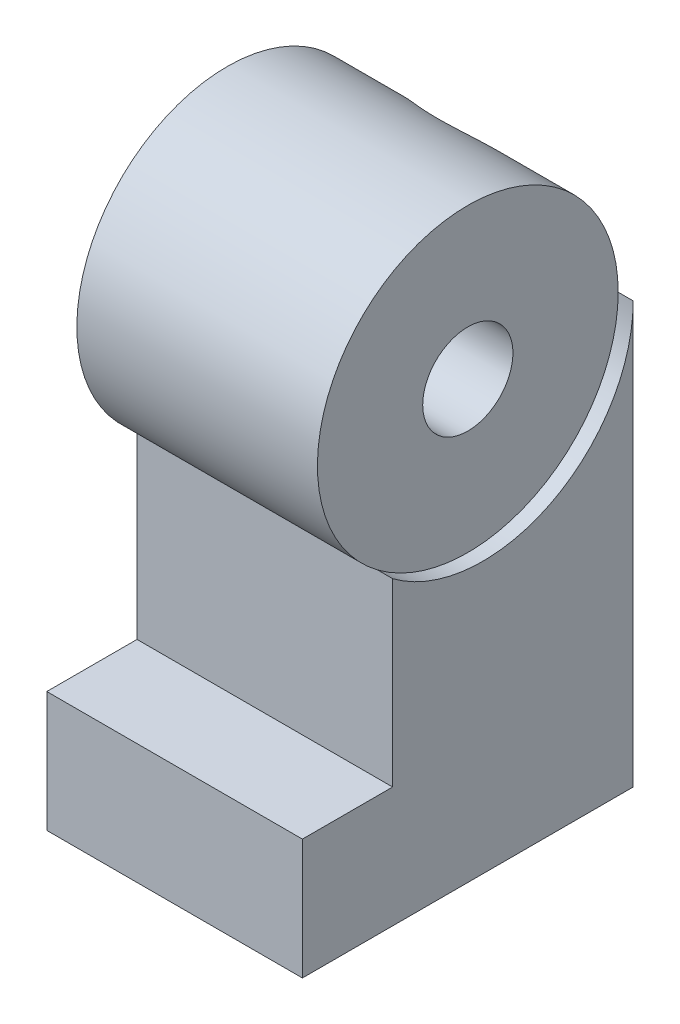
SolidWorks part; units mm, degrees
material "ABS"
ref_plane "Front Plane" through (0, 0, 0) normal (0, 0, 1) x (1, 0, 0)
ref_plane "Top Plane" through (0, 0, 0) normal (0, 1, 0) x (1, 0, 0)
ref_plane "Right Plane" through (0, 0, 0) normal (1, 0, 0) x (0, 0, -1)
sketch "Sketch2" plane through (0, 0, 0) normal (1, 0, 0) x (0, 0, -1)
  line L0 (0, 11.1125) -> (0, 0) construction
  line L1 (-4.3656, 0) -> (4.3656, 0)
  line L2 (-4.3656, 0) -> (-4.3656, 3.175)
  line L3 (-4.3656, 3.175) -> (-1.9844, 3.175)
  line L4 (-1.9844, 3.175) -> (-1.9844, 11.1125)
  line L5 (-1.9844, 11.1125) -> (4.3656, 11.1125)
  line L6 (4.3656, 11.1125) -> (4.3656, 0)
  dimension "D1" = 8.7312
  dimension "D2" = 3.175
  dimension "D3" = 11.1125
  dimension "D4" = 2.3813
extrude "Boss-Extrude4" add sketch "Sketch2" along normal blind 6.7469
sketch "Sketch6" plane through (6.7469, 0, 0) normal (1, 0, 0) x (0, 0, -1)
  line L0 (4.3656, 11.1125) -> (-3.5719, 11.1125) construction
  line L1 (0.3969, 11.1125) -> (0.3969, 15.0813) construction
  circle A0 centre (0.3969, 11.1125) radius 3.9688
  dimension "D1" = 7.9375
  dimension "D2" = 3.9688
extrude "Boss-Extrude5" add sketch "Sketch6" against normal up to surface (6.7469 mm away) up to face at (0, 4.7625, 0.6615)
shell "Shell2" thickness 0.7937
sketch "Sketch7" plane through (0, 0, 0) normal (0, -1, 0) x (1, 0, 0)
  line L0 (5.9531, 3.5719) -> (5.9531, -3.5719) construction
  line L1 (1.1906, -2.3813) -> (5.9531, -2.3813) construction
  line L2 (1.1906, -2.3813) -> (1.1906, 2.3813) construction
  line L3 (1.1906, 2.3813) -> (5.9531, 2.3813) construction
  line L4 (5.9531, -2.3813) -> (5.9531, 2.3813) construction
  line L6 (5.9531, 3.5719) -> (5.9531, 2.3813)
  line L9 (5.9531, 2.3813) -> (1.1906, 2.3813)
  line L10 (0.7937, -3.5719) -> (5.9531, -3.5719)
  line L11 (0.7937, -3.5719) -> (0.7937, 3.5719)
  line L12 (0.7937, 3.5719) -> (5.9531, 3.5719)
  line L14 (1.1906, 2.3813) -> (1.1906, -2.3813)
  line L15 (1.1906, -2.3813) -> (5.9531, -2.3813)
  line L16 (5.9531, -2.3813) -> (5.9531, -3.5719)
  point P4 (5.9531, 0)
  point P17 (1.1906, 0)
  dimension "D1" = 4.7625
extrude "Boss-Extrude6" add sketch "Sketch7" against normal up to next
sketch "Sketch11" plane through (0, 0, 0) normal (-1, 0, 0) x (0, 0, 1)
  circle A0 centre (-0.3969, 11.1125) radius 3.9688
  arc A1 (1.9844, 7.9375) -> (-4.3656, 11.1125) centre (-0.3969, 11.1125) ccw construction
extrude "Cut-Extrude2" cut sketch "Sketch11" against normal offset from surface (0.3969 mm away) 6.35 up to face at (6.7469, 5.0895, 1.0896)
sketch "Sketch13" plane through (6.7469, 0, 0) normal (1, 0, 0) x (0, 0, -1)
  circle A0 centre (0.3969, 11.1125) radius 3.9688
  arc A1 (4.3656, 11.1125) -> (-1.9844, 7.9375) centre (0.3969, 11.1125) ccw construction
extrude "Boss-Extrude11" add sketch "Sketch13" against normal up to surface (6.35 mm away) up to face at (0.3969, 11.1125, -0.3969)
sketch "Sketch14" plane through (0, 0, -4.3656) normal (0, 0, -1) x (-1, 0, 0)
  line L0 (-6.7469, 0) -> (0, 0) construction
  line L1 (-6.7469, 0) -> (-6.7469, 11.1125) construction
  circle A0 centre (-3.5719, 3.9688) radius 2.3813
  circle A1 centre (-3.5719, 11.9062) radius 2.3813
  dimension "D2" = 4.7625
  dimension "D1" = 7.9375
  dimension "D3" = 3.9688
  dimension "D4" = 3.175
extrude "Cut-Extrude3" cut sketch "Sketch14" against normal up to surface (1.9844 mm away) up to face at (3.5719, 3.8377, -2.3812)
sketch "Sketch16" plane through (0, 0, -2.3813) normal (0, 0, -1) x (-1, 0, 0)
  line L0 (-0.3969, 11.1125) -> (-2.7781, 11.1125) construction
  line L2 (-2.7781, 9.6612) -> (-2.7781, 14.1513)
  line L4 (-3.5719, 11.9062) -> (-1.1906, 11.9063) construction
  circle A0 centre (-3.5719, 11.9063) radius 2.3813 construction
  arc A2 (-2.7781, 9.6612) -> (-2.7781, 14.1513) centre (-3.5719, 11.9062) cw
  dimension "D1" = 2.3813
extrude "Cut-Extrude4" cut sketch "Sketch16" against normal blind 3.5719
sketch "Sketch17" plane through (0.3969, 0, 0) normal (-1, 0, 0) x (0, 0, 1)
  circle A0 centre (-0.3969, 11.1125) radius 1.1906
  dimension "D1" = 2.3813
extrude "Cut-Extrude5" cut sketch "Sketch17" against normal blind 2.3813
mirror "Mirror6" about plane through (0, 0, 0) normal (1, 0, 0) of bodies 115
sketch "Sketch18" plane through (0, 0, 0) normal (1, 0, 0) x (0, 0, -1)
  line L1 (-4.3656, 0) -> (4.5244, 0)
  line L2 (-4.3656, 0) -> (-4.3656, 15.24)
  line L3 (-4.3656, 15.24) -> (4.5244, 15.24)
  line L4 (4.5244, 0) -> (4.5244, 15.24)
  dimension "D1" = 8.89
  dimension "D2" = 15.24
extrude "Cut-Extrude6" cut sketch "Sketch18" along normal blind 12.7
